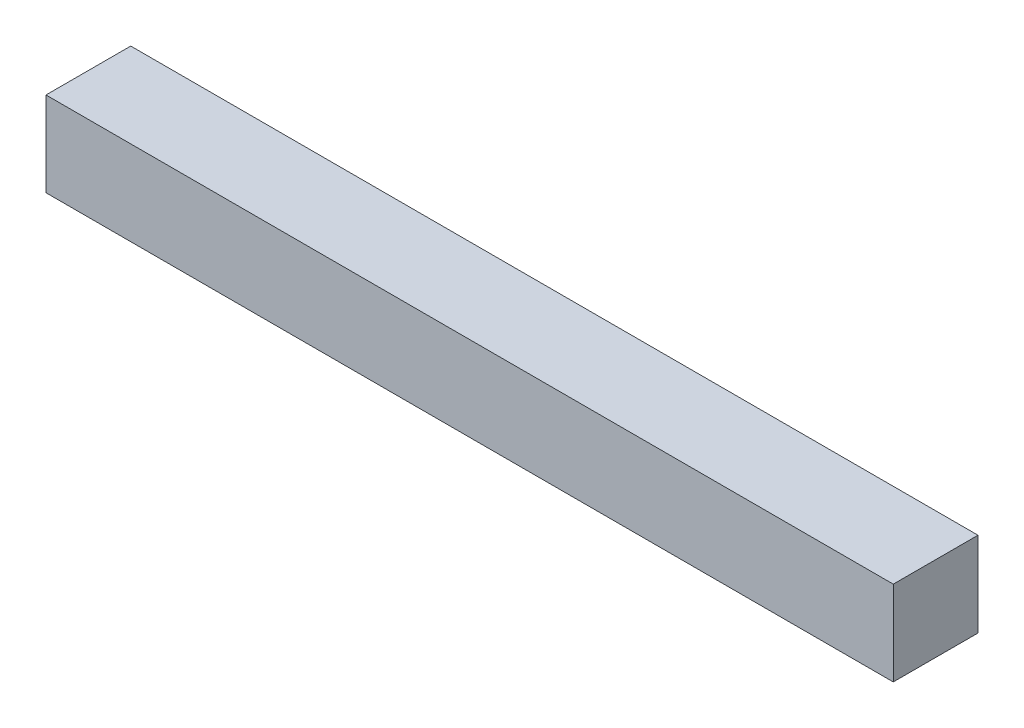
SolidWorks part; units mm, degrees
ref_plane "Front Plane" through (0, 0, 0) normal (0, 0, 1) x (1, 0, 0)
ref_plane "Top Plane" through (0, 0, 0) normal (0, 1, 0) x (1, 0, 0)
ref_plane "Right Plane" through (0, 0, 0) normal (1, 0, 0) x (0, 0, -1)
sketch "Sketch1" plane through (0, 0, 0) normal (1, 0, 0) x (0, 0, -1)
  line L1 (-5, -5) -> (5, -5)
  line L2 (-5, -5) -> (-5, 5)
  line L3 (-5, 5) -> (5, 5)
  line L4 (5, -5) -> (5, 5)
  line L5 (-5, -5) -> (5, 5) construction
  line L6 (-5, 5) -> (5, -5) construction
  point P0 (0, 0)
  dimension "D1" = 10
  dimension "D2" = 10
extrude "Boss-Extrude1" add sketch "Sketch1" along normal blind 100
